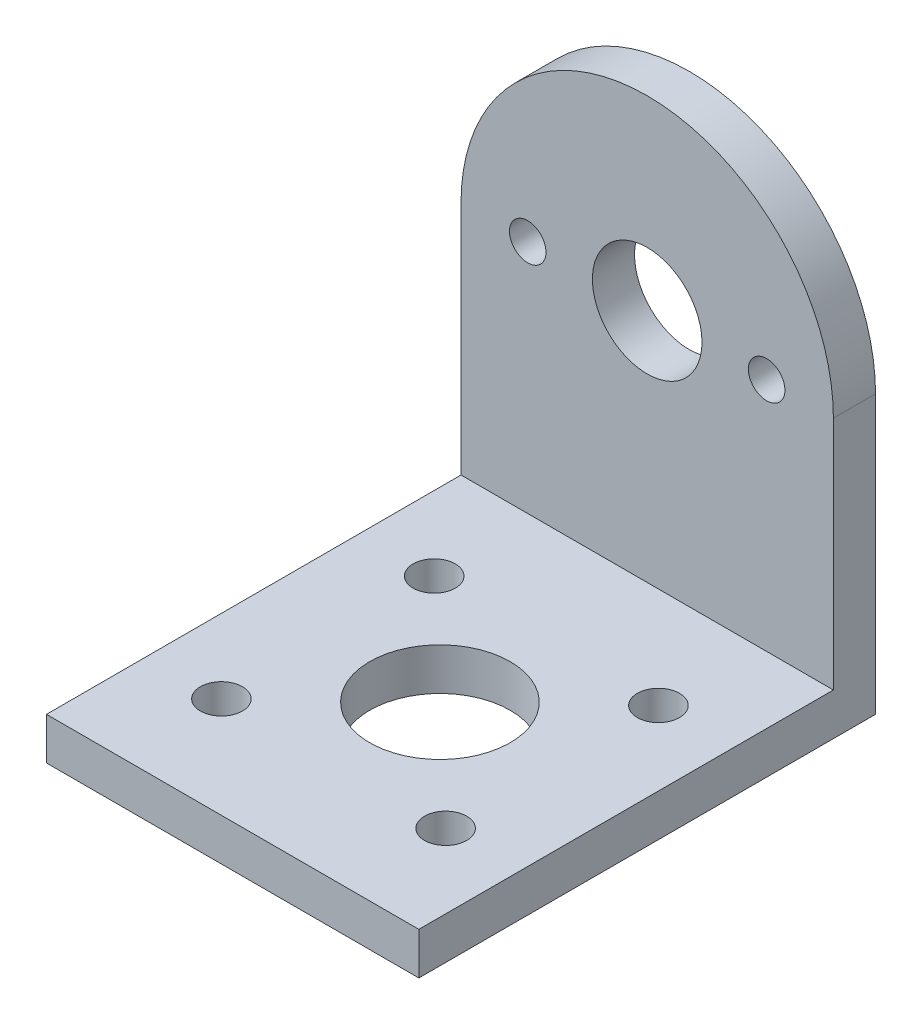
SolidWorks part; units mm, degrees
ref_plane "Front Plane" through (0, 0, 0) normal (0, 0, 1) x (1, 0, 0)
ref_plane "Top Plane" through (0, 0, 0) normal (0, 1, 0) x (1, 0, 0)
ref_plane "Right Plane" through (0, 0, 0) normal (1, 0, 0) x (0, 0, -1)
sketch "Sketch1" plane through (0, 0, 0) normal (0, 0, 1) x (1, 0, 0)
  line L1 (-13.25, -16.5) -> (13.25, -16.5)
  line L2 (-13.25, -16.5) -> (-13.25, 16.5)
  line L3 (-13.25, 16.5) -> (13.25, 16.5)
  line L4 (13.25, -16.5) -> (13.25, 16.5)
  line L5 (-13.25, -16.5) -> (13.25, 16.5) construction
  line L6 (-13.25, 16.5) -> (13.25, -16.5) construction
  circle A1 centre (0, 3.25) radius 13.25
  circle A2 centre (0, 3.25) radius 3.9
  circle A3 centre (-8.5, 3.25) radius 1.3
  circle A4 centre (8.5, 3.25) radius 1.3
  point P0 (0, 0)
  point P12 (0, 3.25)
extrude "Boss-Extrude1" add sketch "Sketch1" along normal blind 3 contours A1 A4 A3 A2 | A1 L2 L1 L4
sketch "Sketch2" plane through (0, -16.5, 0) normal (0, -1, 0) x (1, 0, 0)
  line L3 (-13.25, 32.5) -> (13.25, 32.5)
  line L5 (-13.25, 3) -> (13.25, 3)
  line L6 (-13.25, 3) -> (-13.25, 32.5)
  line L7 (-13.25, 32.5) -> (13.25, 32.5)
  line L8 (13.25, 3) -> (13.25, 32.5)
  line L9 (0, 3) -> (0, 32.5)
  line L10 (-7.9773, 10.1786) -> (7.9773, 10.1786)
  line L11 (-7.9773, 10.1786) -> (-7.9773, 25.3214)
  line L12 (-7.9773, 25.3214) -> (7.9773, 25.3214)
  line L13 (7.9773, 10.1786) -> (7.9773, 25.3214)
  line L14 (-7.9773, 10.1786) -> (7.9773, 25.3214) construction
  line L15 (-7.9773, 25.3214) -> (7.9773, 10.1786) construction
  circle A0 centre (0, 17.75) radius 5
  circle A1 centre (7.9773, 25.3214) radius 1.5
  circle A2 centre (-7.9773, 25.3214) radius 1.5
  circle A3 centre (7.9773, 10.1786) radius 1.5
  circle A4 centre (-7.9773, 10.1786) radius 1.5
  point P16 (-8.4288, 25.3214)
  point P18 (7.9773, 9.7941)
  point P20 (-7.9773, 9.7941)
  line M7 (13.25, 3) -> (-13.25, 3)
extrude "Boss-Extrude2" add sketch "Sketch2" against normal blind 3 contours A4 L11 A2 L12 L9 L3 L6 L5 L10 | A3 L10 L9 L8 L7 L12 A1 L13 M7 | A3 L13 A1 L12 L9 A0 L10 | A4 L10 L9 A0 L12 A2 L11
